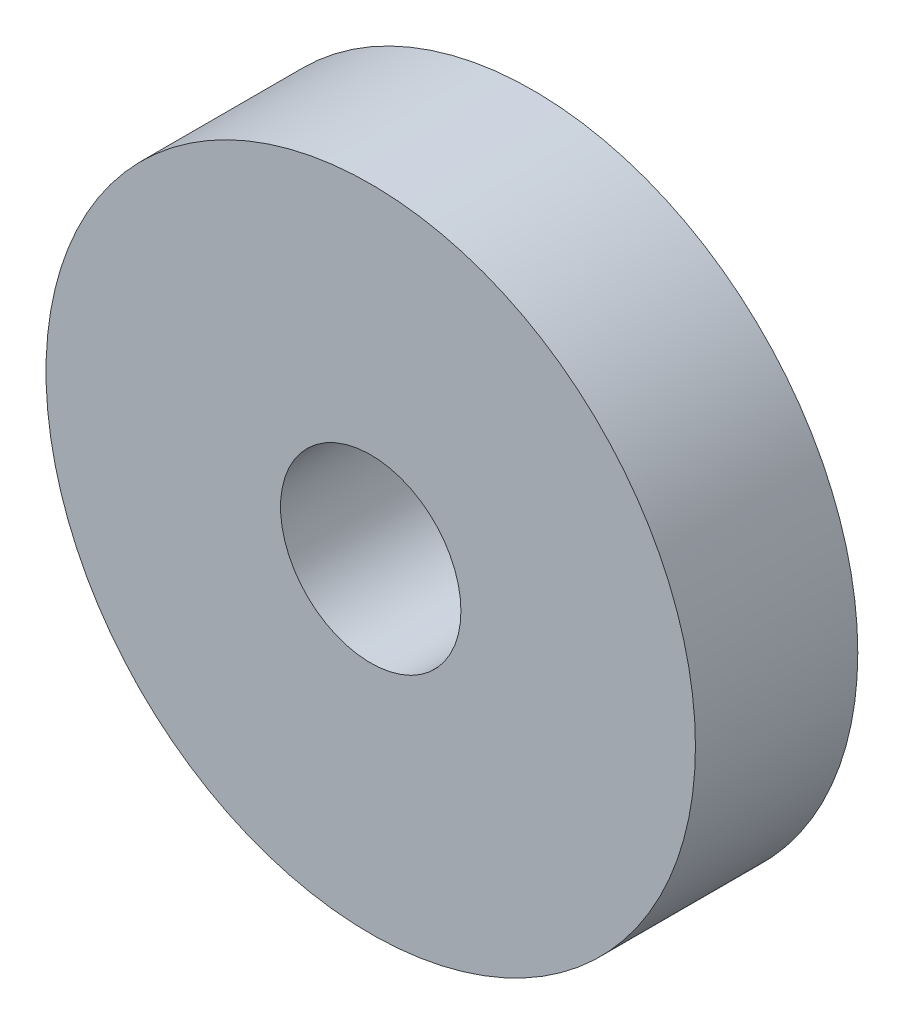
SolidWorks part; units mm, degrees
ref_plane "Plan1" through (0, 0, 0) normal (0, 0, 1) x (1, 0, 0)
ref_plane "Plan2" through (0, 0, 0) normal (0, 1, 0) x (1, 0, 0)
ref_plane "Plan3" through (0, 0, 0) normal (1, 0, 0) x (0, 0, -1)
sketch "Esquisse1" plane through (0, 0, 0) normal (0, 0, 1) x (1, 0, 0)
  circle A0 centre (0, 0) radius 18
  circle A1 centre (0, 0) radius 5
  dimension "D1" = 36
  dimension "D2" = 10
extrude "Base-Extrusion" add sketch "Esquisse1" along normal blind 9
